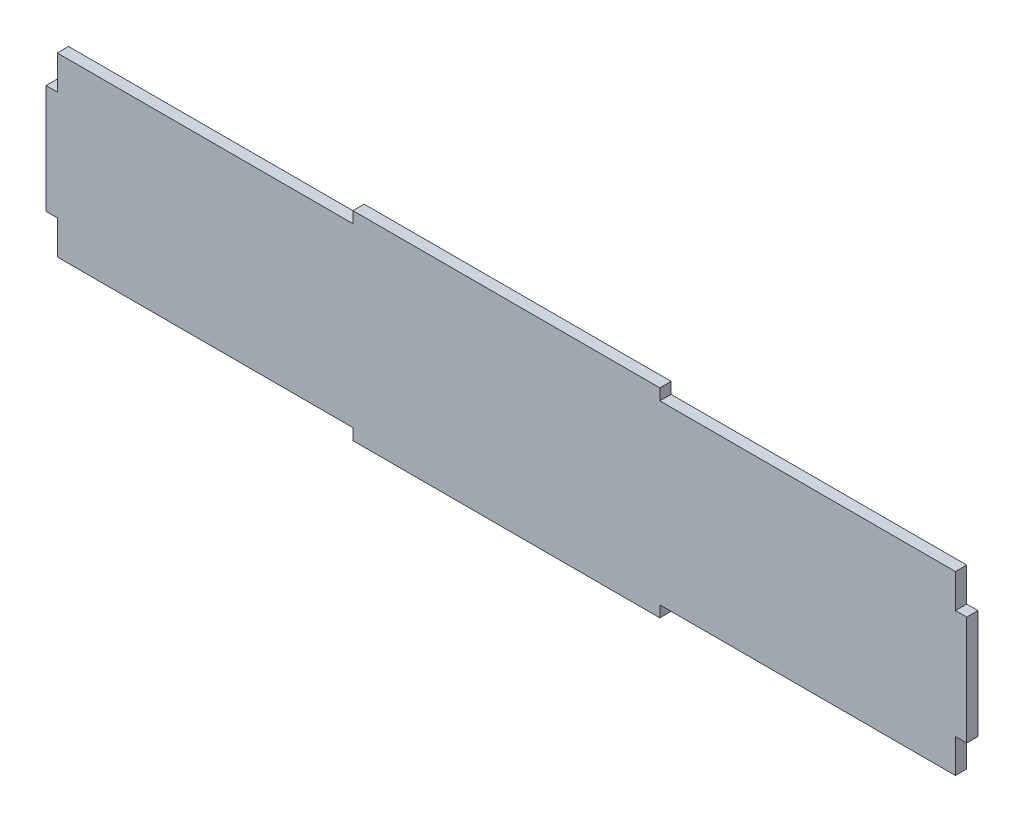
SolidWorks part; units mm, degrees
ref_plane "Front Plane" through (0, 0, 0) normal (0, 0, 1) x (1, 0, 0)
ref_plane "Top Plane" through (0, 0, 0) normal (0, 1, 0) x (1, 0, 0)
ref_plane "Right Plane" through (0, 0, 0) normal (1, 0, 0) x (0, 0, -1)
sketch "Sketch1" plane through (0, 0, 0) normal (0, 0, 1) x (1, 0, 0)
  line L1 (0, 0) -> (490, 0)
  line L2 (0, 0) -> (0, 106.02)
  line L3 (0, 106.02) -> (490, 106.02)
  line L4 (490, 0) -> (490, 106.02)
  dimension "D1" = 490
  dimension "D2" = 106.02
extrude "Boss-Extrude1" add sketch "Sketch1" along normal blind 6
sketch "Sketch2" plane through (0, 0, 6) normal (0, 0, 1) x (1, 0, 0)
  line L1 (490, 0) -> (484, 0)
  line L2 (490, 0) -> (490, 24)
  line L3 (490, 24) -> (484, 24)
  line L4 (484, 0) -> (484, 24)
  line L5 (490, 106.02) -> (484, 106.02)
  line L6 (490, 106.02) -> (490, 82.02)
  line L7 (490, 82.02) -> (484, 82.02)
  line L8 (484, 106.02) -> (484, 82.02)
  line L9 (0, 106.02) -> (6, 106.02)
  line L10 (0, 106.02) -> (0, 82.02)
  line L11 (0, 82.02) -> (6, 82.02)
  line L12 (6, 106.02) -> (6, 82.02)
  line L13 (0, 0) -> (6, 0)
  line L14 (0, 0) -> (0, 24)
  line L15 (0, 24) -> (6, 24)
  line L16 (6, 0) -> (6, 24)
  dimension "D1" = 24
  dimension "D2" = 6
extrude "Cut-Extrude1" cut sketch "Sketch2" against normal through all
sketch "Sketch3" plane through (0, 0, 6) normal (0, 0, 1) x (1, 0, 0)
  line L1 (6, 0) -> (163.3333, 0)
  line L2 (6, 0) -> (6, 6)
  line L3 (6, 6) -> (163.3333, 6)
  line L4 (163.3333, 0) -> (163.3333, 6)
  line L5 (484, 0) -> (326.6667, 0)
  line L6 (484, 0) -> (484, 6)
  line L7 (484, 6) -> (326.6667, 6)
  line L8 (326.6667, 0) -> (326.6667, 6)
  line L9 (6, 106.02) -> (163.3333, 106.02)
  line L10 (6, 106.02) -> (6, 100.02)
  line L11 (6, 100.02) -> (163.3333, 100.02)
  line L12 (163.3333, 106.02) -> (163.3333, 100.02)
  line L13 (484, 106.02) -> (326.6667, 106.02)
  line L14 (484, 106.02) -> (484, 100.02)
  line L15 (484, 100.02) -> (326.6667, 100.02)
  line L16 (326.6667, 106.02) -> (326.6667, 100.02)
  dimension "D1" = 6
  dimension "D2" = 163.3333
  dimension "D3" = 163.3333
extrude "Cut-Extrude2" cut sketch "Sketch3" against normal through all
